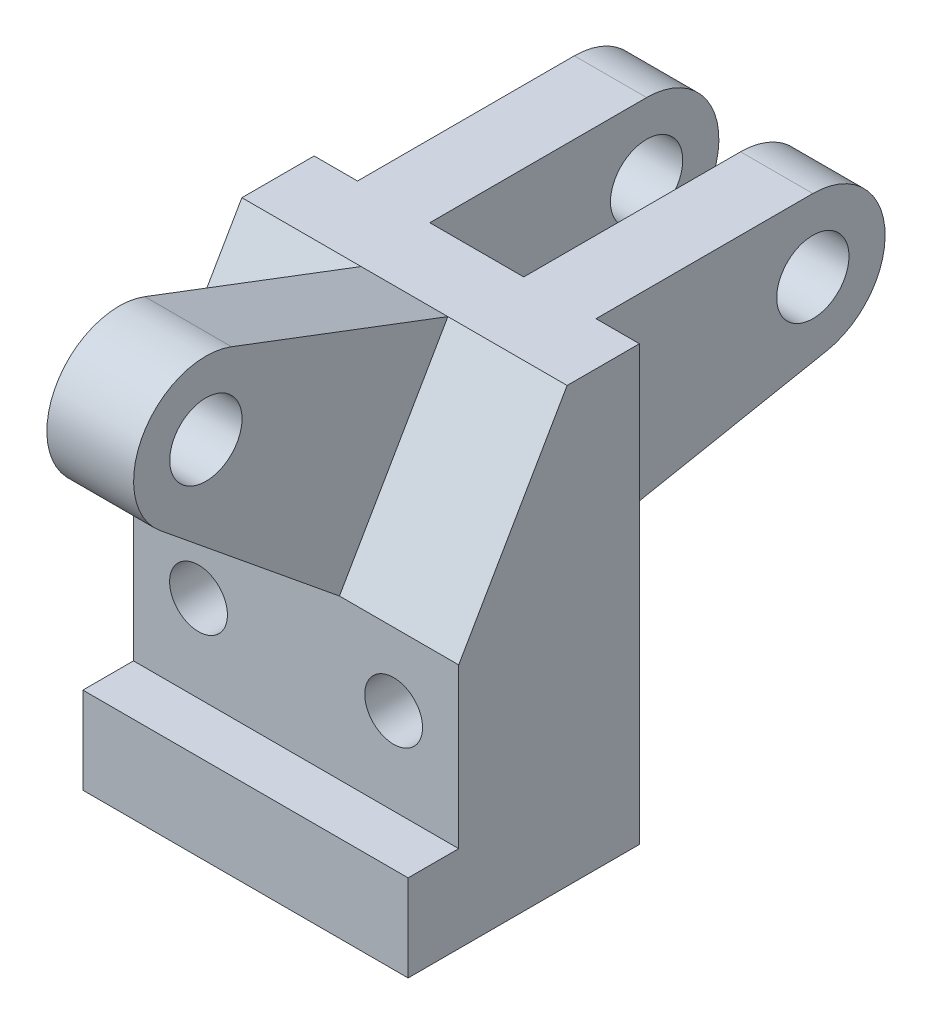
SolidWorks part; units mm, degrees
ref_plane "Front Plane" through (0, 0, 0) normal (0, 0, 1) x (1, 0, 0)
ref_plane "Top Plane" through (0, 0, 0) normal (0, 1, 0) x (1, 0, 0)
ref_plane "Right Plane" through (0, 0, 0) normal (1, 0, 0) x (0, 0, -1)
sketch "Sketch1" plane through (0, 0, 0) normal (1, 0, 0) x (0, 0, -1)
  line L0 (0, 60) -> (0, 0)
  line L1 (0, 0) -> (-32, 0)
  line L2 (-32, 0) -> (-32, 12)
  line L3 (-32, 12) -> (-25, 12)
  line L4 (-25, 12) -> (-25, 34.0192)
  line L5 (-25, 34.0192) -> (-10, 60)
  line L6 (-10, 60) -> (0, 60)
  dimension "D1" = 32
  dimension "D2" = 12
  dimension "D3" = 7
  dimension "D4" = 60
  dimension "D5" = 10
  dimension "D6" = 30
extrude "Boss-Extrude1" add sketch "Sketch1" against normal mid plane 45
sketch "Sketch2" plane through (0, 0, 0) normal (1, 0, 0) x (0, 0, -1)
  line L0 (0, 60) -> (30, 60)
  line L1 (31.9026, 40.1827) -> (0, 34)
  line L2 (0, 0) -> (0, 60) construction
  line L3 (0, 60) -> (0, 34)
  arc A0 (30, 60) -> (31.9026, 40.1827) centre (30, 50) cw
  circle A1 centre (30, 50) radius 5
  dimension "D1" = 10
  dimension "D2" = 10
  dimension "D3" = 30
  dimension "D4" = 26
extrude "Boss-Extrude2" add sketch "Sketch2" along normal mid plane 33
sketch "Sketch3" plane through (0, 60, 0) normal (0, 1, 0) x (1, 0, 0)
  line L0 (-16.5, 30) -> (-16.5, 0) construction
  line L1 (6.5, 0) -> (-6.5, 0)
  line L2 (6.5, 0) -> (6.5, 52.4783)
  line L3 (6.5, 52.4783) -> (-6.5, 52.4783)
  line L4 (-6.5, 0) -> (-6.5, 52.4783)
  line L5 (-22.5, -10) -> (22.5, -10) construction
  line L6 (16.5, 30) -> (16.5, 40) construction
  dimension "D1" = 10
  dimension "D2" = 13
  dimension "D3" = 10
  dimension "D4" = 10
extrude "Cut-Extrude1" cut sketch "Sketch3" against normal through all
ref_plane "Plane1" through (0, 0, 0) normal (1, 0, 0) x (0, 0, -1)
sketch "Sketch4" plane through (0, 0, 0) normal (1, 0, 0) x (0, 0, -1)
  line L0 (-10, 60) -> (-39.9328, 71.3591)
  line L1 (-25, 34.0192) -> (-49.8036, 54.2623)
  line L2 (-10, 60) -> (-25, 34.0192)
  line L3 (-17.5, 47.0096) -> (-61.5213, 72.4253) construction
  circle A0 centre (-43.4808, 62.0096) radius 5
  arc A1 (-39.9328, 71.3591) -> (-49.8036, 54.2623) centre (-43.4808, 62.0096) ccw
  dimension "D1" = 10
  dimension "D2" = 20
  dimension "D3" = 30
extrude "Boss-Extrude3" add sketch "Sketch4" along normal mid plane 12
sketch "Sketch5" plane through (0, 0, 25) normal (0, 0, 1) x (1, 0, 0)
  line L0 (0, 0) -> (0, 62.9864) construction
  line L1 (-22.5, 34.0192) -> (-22.5, 12) construction
  line L2 (-22.5, 12) -> (22.5, 12) construction
  circle A0 centre (-13.5, 24) radius 4
  circle A1 centre (13.5, 24) radius 4
  point P11 (-15.1249, 16.7757)
  dimension "D4" = 8
  dimension "D1" = 27
  dimension "D2" = 9
  dimension "D3" = 12
extrude "Cut-Extrude2" cut sketch "Sketch5" against normal through all
